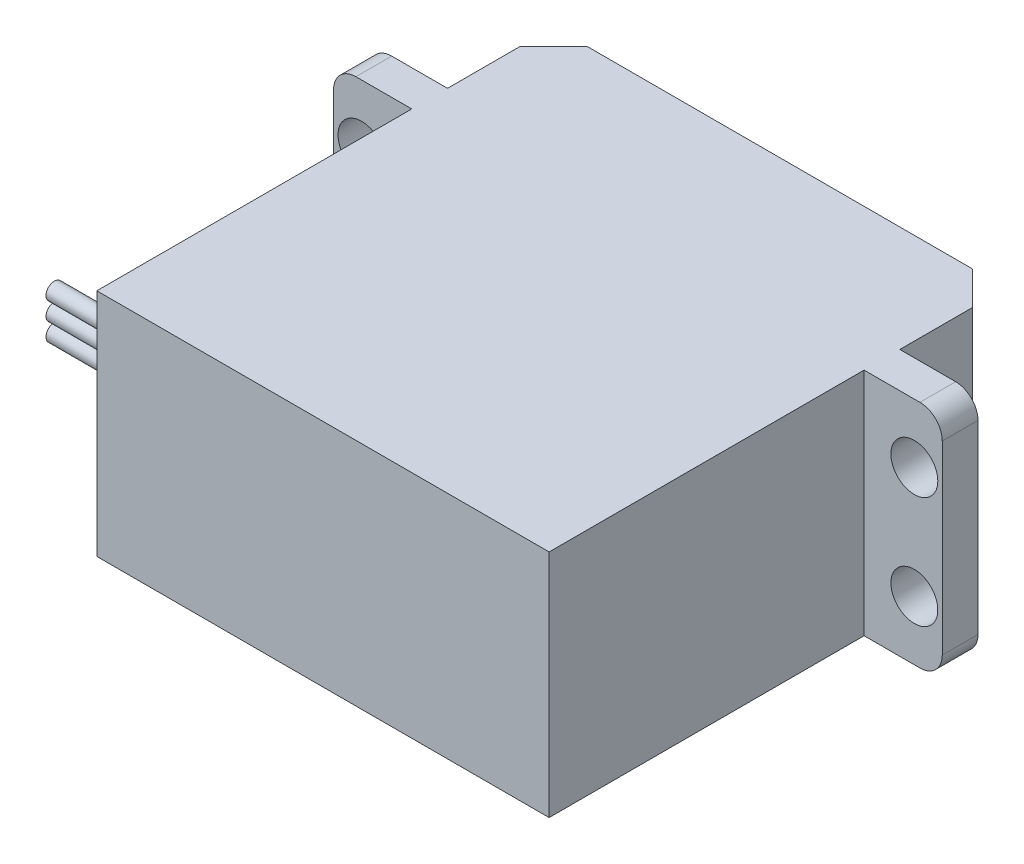
SolidWorks part; units mm, degrees
ref_plane "Plan de face" through (0, 0, 0) normal (0, 0, 1) x (1, 0, 0)
ref_plane "Plan de dessus" through (0, 0, 0) normal (0, 1, 0) x (1, 0, 0)
ref_plane "Plan de droite" through (0, 0, 0) normal (1, 0, 0) x (0, 0, -1)
sketch "Esquisse1" plane through (0, 0, 0) normal (0, 1, 0) x (1, 0, 0)
  line L0 (0, 0) -> (0, 12.7) construction
  line L5 (-17.25, 12.7) -> (17.25, 12.7)
  line L6 (17.25, 12.7) -> (20.25, 9.7)
  line L7 (20.25, 9.7) -> (20.25, -28.2)
  line L8 (20.25, -28.2) -> (-20.25, -28.2)
  line L9 (-20.25, 9.7) -> (-20.25, -28.2)
  line L10 (-17.25, 12.7) -> (-20.25, 9.7)
  point P9 (0, -28.2)
  dimension "D1" = 40.5
  dimension "D2" = 40.9
  dimension "D3" = 3
  dimension "D4" = 3
  dimension "D5" = 28.2
extrude "Boss.-Extru.1" add sketch "Esquisse1" along normal mid plane 20.6
ref_plane "Plan1" through (0, 0, 0) normal (0, 0, 1) x (1, 0, 0)
sketch "Esquisse3" plane through (0, 0, 0) normal (0, 0, 1) x (1, 0, 0)
  line L1 (0, 0) -> (20.25, 0) construction
  line L2 (20.25, 10.3) -> (20.25, -10.3) construction
  line L3 (0, 0) -> (0, 10.3) construction
  line L4 (17.25, 10.3) -> (-17.25, 10.3) construction
  line L16 (20.25, 10.3) -> (27.25, 10.3)
  line L17 (27.25, 10.3) -> (27.25, -10.3)
  line L18 (-20.25, 10.3) -> (-27.25, 10.3)
  line L19 (-27.25, 10.3) -> (-27.25, -10.3)
  line L20 (20.25, 10.3) -> (20.25, -10.3)
  line L21 (20.25, -10.3) -> (27.25, -10.3)
  line L22 (-20.25, -10.3) -> (-27.25, -10.3)
  line L23 (-20.25, 10.3) -> (-20.25, -10.3)
  circle A4 centre (24.75, 5) radius 2.1
  circle A5 centre (24.75, -5) radius 2.1
  circle A8 centre (-24.75, 5) radius 2.1
  circle A9 centre (-24.75, -5) radius 2.1
  point P25 (27.25, 0)
  dimension "D4" = 4.2
  dimension "D1" = 10
  dimension "D2" = 49.5
  dimension "D3" = 54.5
extrude "Boss.-Extru.2" add sketch "Esquisse3" against normal blind 3.2
sketch "Esquisse4" plane through (0, 0, 0) normal (0, 1, 0) x (1, 0, 0)
  line L0 (20.25, 3.2) -> (20.25, 5.1)
  line L1 (20.25, 3.2) -> (20.25, 9.7) construction
  line L3 (25.9, 3.2) -> (25.9, 3.7)
  line L4 (25.9, 3.2) -> (20.25, 3.2)
  line L5 (0, 0) -> (0, 11.6297) construction
  line L8 (-25.9, 3.2) -> (-20.25, 3.2)
  line L9 (27.25, 3.2) -> (20.25, 3.2) construction
  line L10 (25.9, 3.7) -> (21.65, 5.1)
  line L11 (21.65, 5.1) -> (20.25, 5.1)
  line L12 (-25.9, 3.2) -> (-25.9, 3.7)
  line L13 (-25.9, 3.7) -> (-21.65, 5.1)
  line L14 (-21.65, 5.1) -> (-20.25, 5.1)
  line L15 (-20.25, 3.2) -> (-20.25, 5.1)
  dimension "D1" = 51.8
  dimension "D2" = 1.9
  dimension "D3" = 1.4
  dimension "D4" = 0.5
extrude "Boss.-Extru.3" add sketch "Esquisse4" along normal mid plane 1.7
sketch "Esquisse8" plane through (0, 0, -12.7) normal (0, 0, -1) x (-1, 0, 0)
  line L0 (0, 0) -> (10, 0) construction
  line L2 (20.25, 10.3) -> (20.25, -10.3) construction
  circle A0 centre (10, 0) radius 6.75
  dimension "D1" = 13.5
  dimension "D2" = 10.25
extrude "Boss.-Extru.7" add sketch "Esquisse8" along normal blind 1
sketch "Esquisse5" plane through (0, 0, -13.7) normal (0, 0, -1) x (-1, 0, 0)
  line L0 (0, 0) -> (10, 0) construction
  circle A0 centre (10, 0) radius 2.925
  dimension "D1" = 5.85
extrude "Boss.-Extru.4" add sketch "Esquisse5" along normal blind 4.3
fillet "Congé1" radius 2 4 edges at (-27.25, 10.3, -1.6) (-27.25, -10.3, -1.6) (27.25, 10.3, -1.6) (27.25, -10.3, -1.6)
sketch "Esquisse6" plane through (-20.25, 0, 0) normal (-1, 0, 0) x (0, 0, 1)
  line L0 (19.9, 0) -> (0, 0) construction
  line L1 (19.9, 3.4) -> (22.9, 3.4)
  line L2 (19.9, 3.4) -> (19.9, -3.4)
  line L3 (19.9, -3.4) -> (22.9, -3.4)
  line L4 (22.9, 3.4) -> (22.9, -3.4)
  line L5 (28.2, 10.3) -> (28.2, -10.3) construction
  point P7 (21.4, -3.4)
  dimension "D1" = 6.8
  dimension "D2" = 3
  dimension "D3" = 6.8
extrude "Boss.-Extru.5" add sketch "Esquisse6" along normal blind 5.3
sketch "Esquisse7" plane through (-25.55, 0, 0) normal (-1, 0, 0) x (0, 0, 1)
  line L0 (21.4, 3.4) -> (21.4, -3.4) construction
  line L1 (22.9, 3.4) -> (19.9, 3.4) construction
  line L2 (19.9, -3.4) -> (22.9, -3.4) construction
  line L3 (21.4, 0) -> (22.9, 0) construction
  line L4 (22.9, -3.4) -> (22.9, 3.4) construction
  circle A0 centre (21.4, 0) radius 0.75
  circle A1 centre (21.4, 1.6) radius 0.75
  circle A2 centre (21.4, -1.6) radius 0.75
  dimension "D1" = 1.5
  dimension "D2" = 1.6
extrude "Boss.-Extru.6" add sketch "Esquisse7" along normal blind 5.3
hole_wizard "Diamètre du perçage Ø3.0 (3)1" positions "Esquisse10" profile "Esquisse12" hole size "Ø3.0" standard "DIN"
sketch "Esquisse10" plane through (0, 0, -18) normal (0, 0, -1) x (-1, 0, 0)
  point P0 (10, 0)
sketch "Esquisse12" plane through (-10, 0, -18) normal (1, 0, 0) x (0, 1, 0)
  line L0 (0, 0) -> (0, 6.9013)
  line L1 (0, 6.9013) -> (1.5, 6)
  line L2 (1.5, 6) -> (1.5, 0)
  line L5 (1.5, 0) -> (0, 0)
  line L10 (0, 6.9013) -> (-1.5, 6) construction
  line L11 (0, -6.35) -> (0, 107.95) construction
  dimension "Diamètre du perçage" = 3
  dimension "Profondeur du perçage" = 6
  dimension "Angle de pointe" = 118
